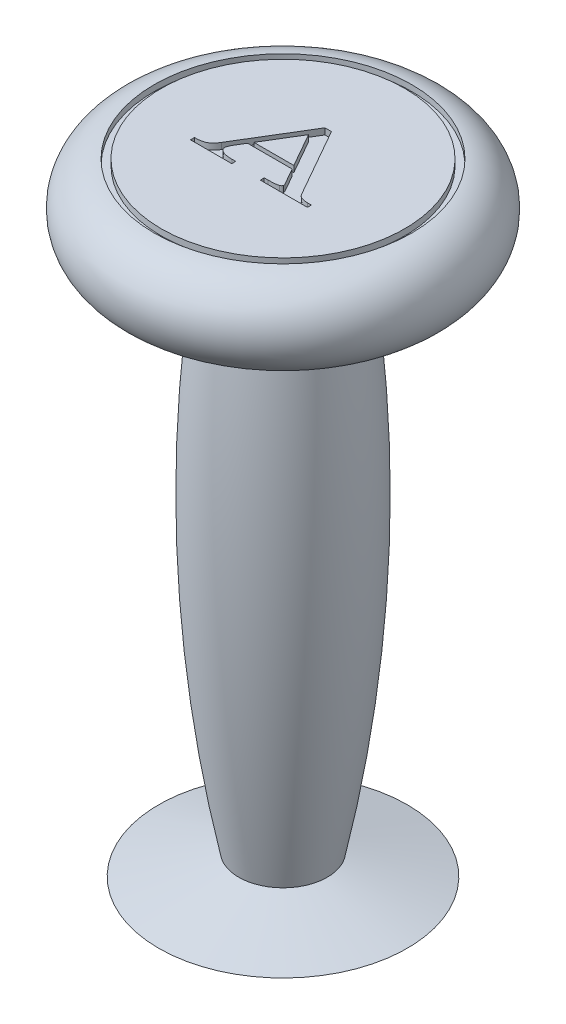
SolidWorks part; units mm, degrees
material "BUTYL"
ref_plane "Front Plane" through (0, 0, 0) normal (0, 0, 1) x (1, 0, 0)
ref_plane "Top Plane" through (0, 0, 0) normal (0, 1, 0) x (1, 0, 0)
ref_plane "Right Plane" through (0, 0, 0) normal (1, 0, 0) x (0, 0, -1)
sketch "Sketch1" plane through (0, 0, 0) normal (0, 0, 1) x (1, 0, 0)
  line L0 (0, 0) -> (0, 150)
  line L1 (0, 150) -> (30, 150)
  line L2 (15, 129.222) -> (30, 129.222)
  line L3 (0, 0) -> (30, 0)
  line L4 (30, 0) -> (10.6815, 5.1764)
  arc A0 (30, 150) -> (30, 129.222) centre (30, 139.611) cw
  arc A1 (15, 129.222) -> (10.6815, 5.1764) centre (-353.0535, 79.9374) cw
  dimension "D1" = 15
revolve "Revolve1" add sketch "Sketch1" angle 360 about L0
sketch "Sketch2" plane through (0, 150, 0) normal (0, 1, 0) x (1, 0, 0)
  circle A0 centre (0, 0) radius 29.3527
  circle A1 centre (0, 0) radius 31.0499
extrude "Cut-Extrude1" cut sketch "Sketch2" against normal blind 1.5
sketch "Sketch3" plane through (0, 150, 0) normal (0, 1, 0) x (1, 0, 0)
  text T0 "A" font "Century Schoolbook" height in points 72
extrude "Cut-Extrude2" cut sketch "Sketch3" against normal blind 1.5
sketch "Sketch4" plane through (0, 0, 0) normal (0, -1, 0) x (-1, 0, 0)
  circle A0 centre (0, 0) radius 10
extrude "Cut-Extrude3" cut sketch "Sketch4" against normal blind 15
equation "\"o.15\"=1"
